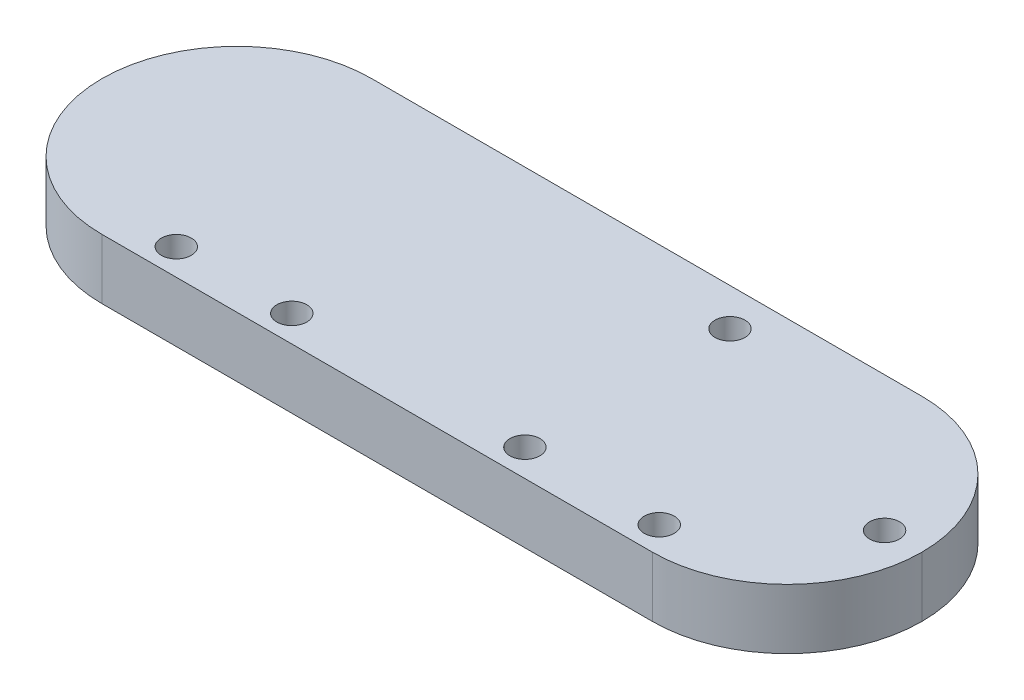
SolidWorks part; units mm, degrees
ref_plane "Спереди" through (0, 0, 0) normal (0, 0, 1) x (1, 0, 0)
ref_plane "Сверху" through (0, 0, 0) normal (0, 1, 0) x (1, 0, 0)
ref_plane "Справа" through (0, 0, 0) normal (1, 0, 0) x (0, 0, -1)
sketch "Эскиз1" plane through (0, 0, 0) normal (0, 1, 0) x (1, 0, 0)
  line L1 (-18.35, -8.99) -> (18.35, -8.99)
  line L2 (-27.33, -0.01) -> (-27.33, 0.01)
  line L3 (-18.35, 8.99) -> (18.35, 8.99)
  line L4 (27.33, -0.01) -> (27.33, 0.01)
  line L5 (-27.33, -8.99) -> (27.33, 8.99) construction
  line L6 (-27.33, 8.99) -> (27.33, -8.99) construction
  arc A0 (-18.35, 8.99) -> (-27.33, 0.01) centre (-18.35, 0.01) ccw
  arc A1 (-27.33, -0.01) -> (-18.35, -8.99) centre (-18.35, -0.01) ccw
  arc A2 (18.35, -8.99) -> (27.33, -0.01) centre (18.35, -0.01) ccw
  arc A3 (27.33, 0.01) -> (18.35, 8.99) centre (18.35, 0.01) ccw
  point P0 (0, 0)
  dimension "D3" = 8.98
  dimension "D1" = 54.66
  dimension "D2" = 17.98
extrude "Бобышка-Вытянуть1" add sketch "Эскиз1" along normal blind 4
sketch "Эскиз2" plane through (0, 4, 0) normal (0, 1, 0) x (1, 0, 0)
  line L0 (18.35, 8.99) -> (-18.35, 8.99) construction
  circle A0 centre (24.83, 0.0025) radius 1
  circle A1 centre (8.04, 6.49) radius 1
  circle A2 centre (16.9932, -7.179) radius 1
  circle A3 centre (8.04, -7.179) radius 1
  circle A4 centre (-15.1511, -7.2251) radius 1
  circle A5 centre (-7.4521, -7.2251) radius 1
  dimension "D1" = 2.5
  dimension "D2" = 2
  dimension "D3" = 16.79
  dimension "D4" = 2.5
extrude "Вырез-Вытянуть1" cut sketch "Эскиз2" against normal blind 4
